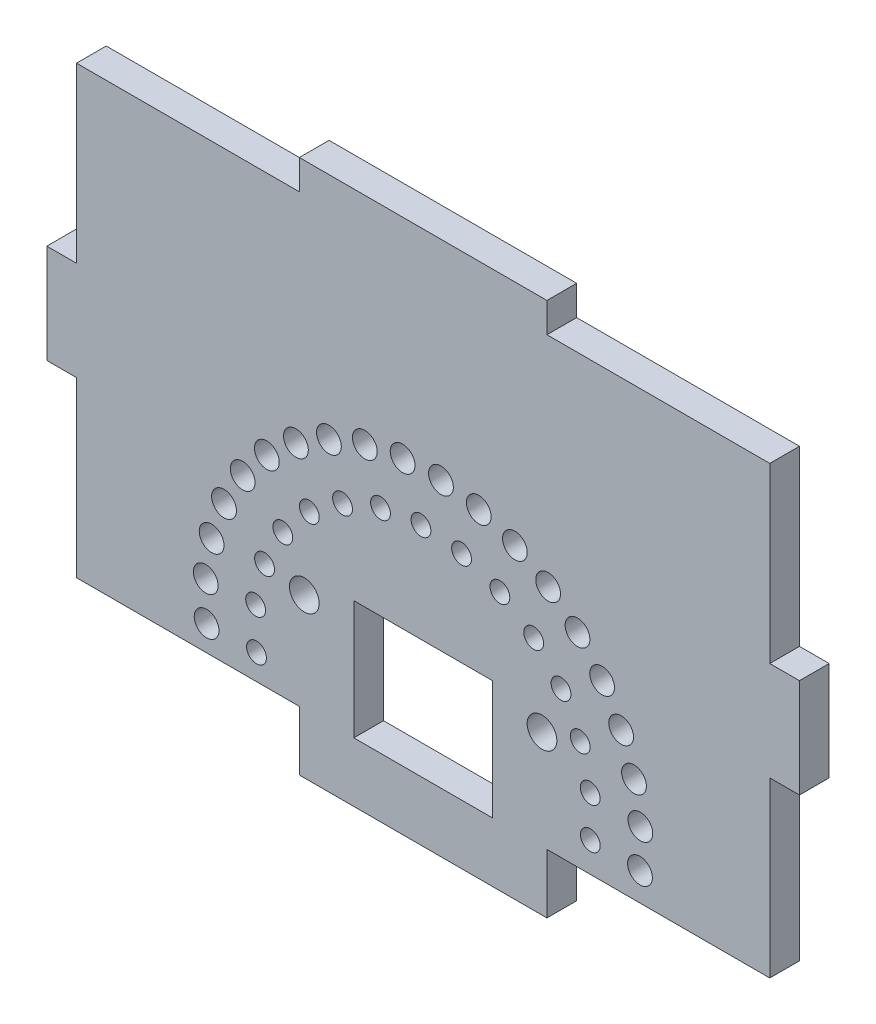
SolidWorks part; units mm, degrees
ref_plane "Front Plane" through (0, 0, 0) normal (0, 0, 1) x (1, 0, 0)
ref_plane "Top Plane" through (0, 0, 0) normal (0, 1, 0) x (1, 0, 0)
ref_plane "Right Plane" through (0, 0, 0) normal (1, 0, 0) x (0, 0, -1)
sketch "Sketch1" plane through (0, 0, 0) normal (0, 0, 1) x (1, 0, 0)
  line L0 (0, 0) -> (22.5, 0)
  line L1 (22.5, 0) -> (22.5, -6)
  line L2 (22.5, -6) -> (47.5, -6)
  line L3 (47.5, -6) -> (47.5, 0)
  line L4 (47.5, 0) -> (70, 0)
  line L5 (70, 0) -> (70, 17.5)
  line L6 (70, 17.5) -> (73, 17.5)
  line L7 (73, 17.5) -> (73, 27.5)
  line L8 (73, 27.5) -> (70, 27.5)
  line L9 (70, 27.5) -> (70, 45)
  line L10 (70, 45) -> (47.5, 45)
  line L11 (47.5, 45) -> (47.5, 48)
  line L12 (47.5, 48) -> (22.5, 48)
  line L13 (22.5, 48) -> (22.5, 45)
  line L14 (22.5, 45) -> (0, 45)
  line L15 (0, 45) -> (0, 27.5)
  line L16 (0, 27.5) -> (-3, 27.5)
  line L17 (-3, 27.5) -> (-3, 17.5)
  line L18 (-3, 17.5) -> (0, 17.5)
  line L19 (0, 17.5) -> (0, 0)
  dimension "D1" = 10
  dimension "D2" = 25
  dimension "D3" = 3
  dimension "D4" = 70
  dimension "D5" = 45
  dimension "D6" = 6
extrude "Boss-Extrude1" add sketch "Sketch1" along normal blind 3
sketch "Sketch2" plane through (0, 0, 3) normal (0, 0, 1) x (1, 0, 0)
  line L0 (70, 0) -> (70, 17.5) construction
  line L1 (28, 12) -> (42, 12)
  line L2 (28, 12) -> (28, 0)
  line L3 (28, 0) -> (42, 0)
  line L4 (42, 12) -> (42, 0)
  line L5 (47.5, 0) -> (70, 0) construction
  circle A0 centre (23, 10) radius 1.5
  circle A1 centre (47, 10) radius 1.5
  dimension "D1" = 3
  dimension "D3" = 23
  dimension "D4" = 10
  dimension "D8" = 2
  dimension "D2" = 24
  dimension "D5" = 14
  dimension "D6" = 12
  dimension "D7" = 28
extrude "Cut-Extrude1" cut sketch "Sketch2" against normal through all
sketch "Sketch3" plane through (0, 0, 0) normal (0, 0, -1) x (-1, 0, 0)
  line L0 (-28, 0) -> (-42, 0) construction
  line L1 (-28, 12) -> (-28, 0) construction
  line L2 (-47.5, 0) -> (-70, 0) construction
  line L3 (0, 0) -> (-22.5, 0) construction
  circle A0 centre (-35, 5) radius 17 construction
  circle A1 centre (-51.8819, 3) radius 1
  circle A2 centre (-51.867, 7.1225) radius 1
  circle A3 centre (-50.8601, 11.1202) radius 1
  circle A4 centre (-48.9206, 14.7579) radius 1
  circle A5 centre (-46.1624, 17.8219) radius 1
  circle A6 centre (-42.7478, 20.1318) radius 1
  circle A7 centre (-38.8776, 21.5519) radius 1
  circle A8 centre (-34.7794, 21.9986) radius 1
  circle A9 centre (-30.6941, 21.4456) radius 1
  circle A10 centre (-26.862, 19.9256) radius 1
  circle A11 centre (-23.5085, 17.5278) radius 1
  circle A12 centre (-20.8308, 14.3933) radius 1
  circle A13 centre (-18.9864, 10.7064) radius 1
  circle A14 centre (-18.0836, 6.684) radius 1
  circle A15 centre (-18.1757, 2.5625) radius 1
  circle A16 centre (-35, 5) radius 22 construction
  circle A17 centre (-13.1355, 2.5625) radius 1.25
  circle A18 centre (-13.047, 6.4366) radius 1.25
  circle A19 centre (-13.6396, 10.2661) radius 1.25
  circle A20 centre (-14.8949, 13.9323) radius 1.25
  circle A21 centre (-16.774, 17.3213) radius 1.25
  circle A22 centre (-19.2186, 20.328) radius 1.25
  circle A23 centre (-22.1529, 22.8592) radius 1.25
  circle A24 centre (-25.4857, 24.8363) radius 1.25
  circle A25 centre (-29.1137, 26.1979) radius 1.25
  circle A26 centre (-32.9243, 26.9019) radius 1.25
  circle A27 centre (-36.7994, 26.9263) radius 1.25
  circle A28 centre (-40.6186, 26.2704) radius 1.25
  circle A29 centre (-44.2635, 24.9547) radius 1.25
  circle A30 centre (-47.6209, 23.0198) radius 1.25
  circle A31 centre (-50.5869, 20.5258) radius 1.25
  circle A32 centre (-53.0692, 17.5501) radius 1.25
  circle A33 centre (-54.9909, 14.1851) radius 1.25
  circle A34 centre (-56.2923, 10.535) radius 1.25
  circle A35 centre (-56.9332, 6.7133) radius 1.25
  circle A36 centre (-56.8935, 2.8384) radius 1.25
  point P40 (-35, 5)
  point P45 (0, 0)
  point P46 (0, 0)
  point P84 (-35, 5)
  dimension "D1" = 34
  dimension "D2" = 5
  dimension "D3" = 7
  dimension "D4" = 2
  dimension "D5" = 3
  dimension "D8" = 44
  dimension "D9" = 2.5
  dimension "D10" = 2.5625
  dimension "D12" = 6.4366
  dimension "D7" = 7.1225
  dimension "D6" = 15
  dimension "D11" = 20
extrude "Cut-Extrude2" cut sketch "Sketch3" against normal through all
